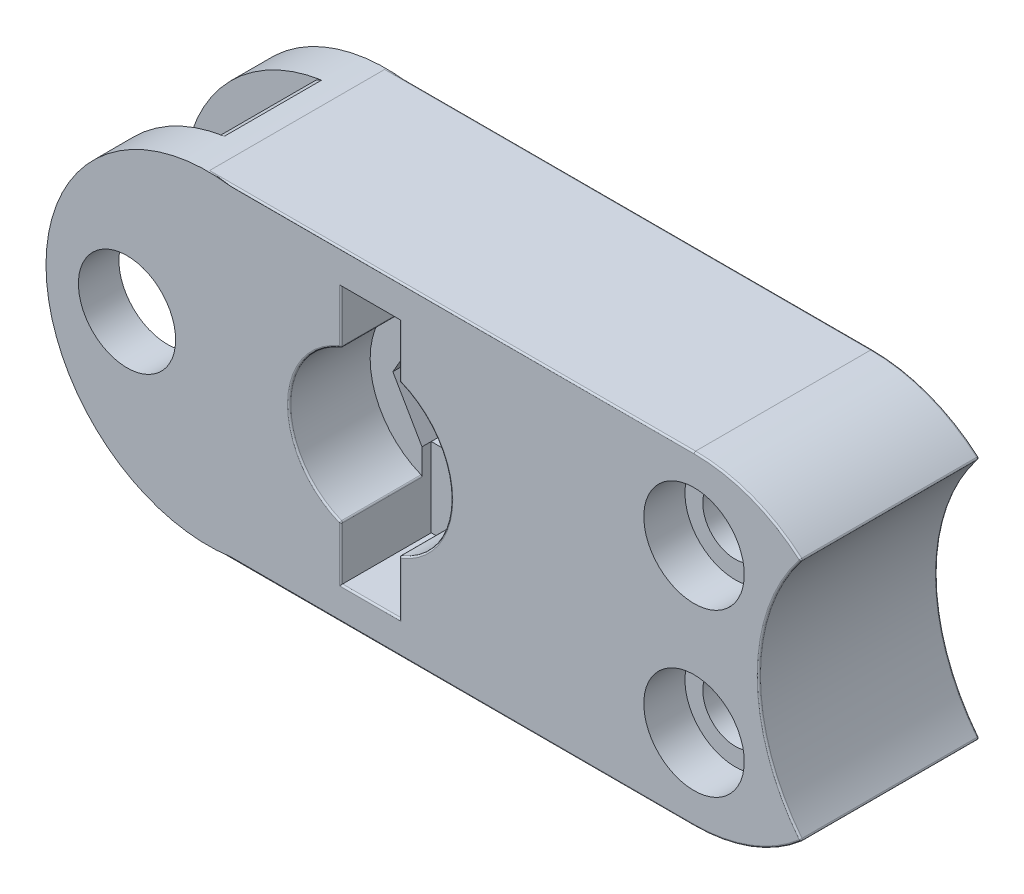
SolidWorks part; units mm, degrees
ref_plane "前视基准面" through (0, 0, 0) normal (0, 0, 1) x (1, 0, 0)
ref_plane "上视基准面" through (0, 0, 0) normal (0, 1, 0) x (1, 0, 0)
ref_plane "右视基准面" through (0, 0, 0) normal (1, 0, 0) x (0, 0, -1)
sketch "草图1" plane through (0, 0, 0) normal (0, 0, 1) x (1, 0, 0)
  line L0 (-100.0924, 0) -> (199.9076, 0) construction
  line L1 (-100.0924, 100) -> (199.9076, 100)
  line L2 (-100.0924, -100) -> (199.9076, -100)
  arc A0 (-100.0924, 100) -> (-100.0924, -100) centre (-100.0924, 0) ccw
  arc A1 (199.9076, -100) -> (199.9076, 100) centre (199.9076, 0) ccw
  circle A2 centre (-110.0924, 0) radius 40
  point P3 (49.9076, 0)
  point P10 (-200.0924, 0)
  dimension "D3" = 90
  dimension "D1" = 300
  dimension "D2" = 200
extrude "凸台-拉伸1" add sketch "草图1" along normal blind 110
ref_plane "基准面4" through (-100, 0, 0) normal (1, 0, 0) x (0, 0, -1)
sketch "草图2" plane through (-100, 0, 0) normal (1, 0, 0) x (0, 0, -1)
  line L0 (-110, 100) -> (-110, -100) construction
  circle A0 centre (-95, 0) radius 3
  circle A1 centre (-75, 0) radius 3
  circle A2 centre (-55, 0) radius 3
  dimension "D1" = 6
  dimension "D2" = 15
  dimension "D3" = 3
extrude "切除-拉伸2" cut sketch "草图2" against normal blind 150
sketch "草图3" plane through (0, 0, 110) normal (0, 0, 1) x (1, 0, 0)
  circle A0 centre (0, 0) radius 50
  dimension "D1" = 0
extrude "切除-拉伸3" cut sketch "草图3" against normal blind 50
sketch "草图4" plane through (0, 0, 60) normal (0, 0, 1) x (1, 0, 0)
  line L1 (36, 0) -> (18, 31.1769)
  line L2 (18, 31.1769) -> (-18, 31.1769)
  line L3 (-18, 31.1769) -> (-36, 0)
  line L4 (-36, 0) -> (-18, -31.1769)
  line L5 (-18, -31.1769) -> (18, -31.1769)
  line L6 (18, -31.1769) -> (36, 0)
  circle A0 centre (0, 0) radius 36 construction
extrude "切除-拉伸4" cut sketch "草图4" against normal blind 10
sketch "草图5" plane through (0, 0, 50) normal (0, 0, 1) x (1, 0, 0)
  line L1 (18, 80) -> (-18, 80)
  line L2 (18, 80) -> (18, -80)
  line L3 (18, -80) -> (-18, -80)
  line L4 (-18, 80) -> (-18, -80)
  line L5 (18, 80) -> (-18, -80) construction
  line L6 (18, -80) -> (-18, 80) construction
  point P0 (0, 0)
  dimension "D1" = 36
  dimension "D2" = 160
extrude "切除-拉伸7" cut sketch "草图5" along normal blind 122
sketch "草图6" plane through (0, 0, 50) normal (0, 0, 1) x (1, 0, 0)
  line L1 (36, 0) -> (18, 31.1769)
  line L2 (18, 31.1769) -> (-18, 31.1769)
  line L3 (-18, 31.1769) -> (-36, 0)
  line L4 (-36, 0) -> (-18, -31.1769)
  line L5 (-18, -31.1769) -> (18, -31.1769)
  line L6 (18, -31.1769) -> (36, 0)
  circle A0 centre (0, 0) radius 36 construction
extrude "切除-拉伸8" cut sketch "草图6" against normal blind 10
sketch "草图7" plane through (0, 0, 50) normal (0, 0, 1) x (1, 0, 0)
  line L0 (-18, 80) -> (18, 80) construction
  circle A0 centre (0, 62) radius 3
  point P4 (0, 80)
  dimension "D1" = 6
  dimension "D2" = 18
extrude "切除-拉伸9" cut sketch "草图7" against normal blind 10
mirror "镜向1" about plane through (0, 0, 0) normal (0, 1, 0) of "切除-拉伸9"
sketch "草图8" plane through (0, 0, 110) normal (0, 0, 1) x (1, 0, 0)
  line L0 (199.9076, 100) -> (199.9076, -100)
  line L1 (199.9076, -100) -> (199.9076, 0)
  line L2 (199.9076, 0) -> (199.9076, 100)
  circle A0 centre (199.9076, 50) radius 12.5
  dimension "D1" = 25
extrude "切除-拉伸12" cut sketch "草图8" against normal blind 200 contours L2 A0 | L2 A0
sketch "草图9" plane through (0, 0, 110) normal (0, 0, 1) x (1, 0, 0)
  circle A0 centre (199.9076, 50) radius 31
  circle M2 centre (199.9076, 50) radius 12.5
extrude "切除-拉伸13" cut sketch "草图9" against normal blind 25.4 contours A0 M2
ref_plane "基准面5" through (0, 0, 55) normal (0, 0, 1) x (1, 0, 0)
mirror "镜向3" about plane through (0, 0, 0) normal (0, 1, 0) of "切除-拉伸13", "切除-拉伸12" second plane through (0, 0, 55) second plane normal (0, 0, 1)
sketch "草图10" plane through (0, 0, 40) normal (0, 0, 1) x (1, 0, 0)
  line L1 (36, 0) -> (18, 31.1769)
  line L2 (18, 31.1769) -> (-18, 31.1769)
  line L3 (-18, 31.1769) -> (-36, 0)
  line L4 (-36, 0) -> (-18, -31.1769)
  line L5 (-18, -31.1769) -> (18, -31.1769)
  line L6 (18, -31.1769) -> (36, 0)
  line L7 (-18, 83.4512) -> (18, 83.4512)
  line L8 (-18, 83.4512) -> (-18, -83.4512)
  line L9 (-18, -83.4512) -> (18, -83.4512)
  line L10 (18, 83.4512) -> (18, -83.4512)
  line L11 (-18, 83.4512) -> (18, -83.4512) construction
  line L12 (-18, -83.4512) -> (18, 83.4512) construction
  circle A0 centre (0, 0) radius 36 construction
  circle A1 centre (0, 0) radius 36
  circle A2 centre (0, 0) radius 50
  line M7 (18, -31.1769) -> (36, 0)
  line M8 (36, 0) -> (18, 31.1769)
  line M10 (-18, 31.1769) -> (-36, 0)
  line M11 (-36, 0) -> (-18, -31.1769)
extrude "凸台-拉伸2" add sketch "草图10" along normal blind 4.3 contours L10 A2 A1 | L8 A2 A1 | A1 M8 | A1 M7 | A1 M11 | A1 M10
sketch "草图11" plane through (0, 0, 50) normal (0, 0, 1) x (1, 0, 0)
  line L0 (-18, 31.1769) -> (18, 31.1769)
  line L1 (-18, 80) -> (18, 80)
  line L2 (-18, 80) -> (-18, -80)
  line L3 (-18, -80) -> (18, -80)
  line L4 (18, 80) -> (18, -80)
  line L5 (-18, 80) -> (18, -80) construction
  line L6 (-18, -80) -> (18, 80) construction
  circle A0 centre (0, 62) radius 3
  point P0 (0, 0)
  circle M1 centre (0, 62) radius 3
  line M2 (-18, 31.1769) -> (18, 31.1769)
  line M3 (18, 31.1769) -> (18, 80)
  line M4 (18, 80) -> (-18, 80)
  line M5 (-18, 80) -> (-18, 31.1769)
extrude "凸台-拉伸3" add sketch "草图11" along normal blind 4.3 contours M5 M2 M3 M4 M1
mirror "镜向4" about plane through (0, 0, 0) normal (0, 1, 0) of "凸台-拉伸3"
sketch "草图12" plane through (0, 0, 110) normal (0, 0, 1) x (1, 0, 0)
  line L0 (199.9076, 100) -> (199.9076, -100)
  line L1 (199.9076, 0) -> (359.9076, 0)
  circle A0 centre (359.9076, 0) radius 120
  arc M6 (199.9076, -100) -> (199.9076, 100) centre (199.9076, 0) ccw
  dimension "D1" = 160
extrude "切除-拉伸14" cut sketch "草图12" against normal blind 200 contours L1 A0 M6 | A0 L1 M6
sketch "草图13" plane through (0, 0, 84.6) normal (0, 0, 1) x (1, 0, 0)
  circle A0 centre (199.9076, 50) radius 20
extrude "切除-拉伸15" cut sketch "草图13" against normal blind 200
mirror "镜向5" about plane through (0, 0, 0) normal (0, 1, 0) of "切除-拉伸15"
sketch "草图14" plane through (0, 0, 110) normal (0, 0, 1) x (1, 0, 0)
  circle A0 centre (-70.0924, 0) radius 108.5853
  circle A1 centre (-110.0924, 0) radius 40 construction
  arc M5 (-100.0924, 100) -> (-100.0924, -100) centre (-100.0924, 0) ccw
extrude "切除-拉伸16" cut sketch "草图14" against normal blind 200 contours A0 M5
fillet "圆角1" radius 1 16 edges at (-107.5362, -99.7226, 0) (49.9076, -100, 0) (-107.5362, 99.7226, 0) (49.9076, 100, 0) (-107.5362, -99.7226, 110) (49.9076, -100, 110) (-107.5362, 99.7226, 110) (49.9076, 100, 110) (235.3292, -93.5164, 0) (239.9076, 0, 0) (235.3292, 93.5164, 0) (266.1576, 74.9062, 55) (266.1576, -74.9062, 55) (235.3292, -93.5164, 110) (239.9076, 0, 110) (235.3292, 93.5164, 110)
fillet "圆角2" radius 1 11 edges at (18, -46.6476, 85) (18, 46.6476, 85) (18, 63.3238, 110) (-18, 63.3238, 110) (-18, -46.6476, 85) (-18, 46.6476, 85) (-50, 0, 110) (-18, -63.3238, 110) (0, -80, 110) (18, -63.3238, 110) (50, 0, 110)
sketch "草图18" plane through (0, 0, 110) normal (0, 0, 1) x (1, 0, 0)
  circle A0 centre (-110.0924, 0) radius 127.2546
  circle A1 centre (-162.4332, 0) radius 108.3882
  arc M10 (-118.2554, 97.3196) -> (-118.2554, -97.3196) centre (-70.0924, 0) ccw
  arc M11 (-118.2554, -97.3196) -> (-100.0924, -99) centre (-100.0924, 0) ccw
  arc M17 (-100.0924, 99) -> (-118.2554, 97.3196) centre (-100.0924, 0) ccw
  circle M20 centre (-110.0924, 0) radius 40
extrude "凸台-拉伸6" add sketch "草图18" against normal blind 110 contours A1 M11 M17 M10 M20 | M20
sketch "草图19" plane through (0, 0, 110) normal (0, 0, 1) x (1, 0, 0)
  line L0 (-100.0924, 99) -> (-100.0924, -100)
  circle A0 centre (-100.0924, 0) radius 100
  arc M1 (-100.0924, 99) -> (-118.2554, 97.3196) centre (-100.0924, 0) ccw
  arc M2 (-118.2554, 97.3196) -> (-118.2554, -97.3196) centre (-70.0924, 0) ccw
  arc M3 (-118.2554, -97.3196) -> (-100.0924, -99) centre (-100.0924, 0) ccw
extrude "切除-拉伸20" cut sketch "草图19" against normal blind 110 contours L0 M1 M2 M3
sketch "草图20" plane through (0, 0, 110) normal (0, 0, 1) x (1, 0, 0)
  line L0 (-100.0924, 99) -> (-100.0924, -99) construction
  line L1 (-100.0924, 99) -> (-100.0924, -99)
  circle A0 centre (-100.0924, 0) radius 100
  line M11 (199.9076, 99) -> (-100.0924, 99)
  line M12 (-100.0924, 99) -> (-100.0924, -99)
  line M13 (-100.0924, -99) -> (199.9076, -99)
extrude "凸台-拉伸7" add sketch "草图20" against normal blind 25 contours A0 M11 M13 M12
sketch "草图21" plane through (0, 0, 110) normal (0, 0, 1) x (1, 0, 0)
  line L0 (-100.0924, 100) -> (-100.0924, -100)
  line L1 (-100.0924, -100) -> (-100.0924, 0)
  line L2 (-100.0924, 0) -> (-200.0924, 0)
  arc A0 (-85.9857, 99) -> (-85.9857, -99) centre (-100.0924, 0) ccw construction
  circle A1 centre (-150.0924, 0) radius 30
  dimension "D1" = 60
extrude "切除-拉伸21" cut sketch "草图21" against normal blind 25 contours L2 A1 | L2 A1
mirror "镜向7" about plane through (0, 0, 55) normal (0, 0, 1) of "凸台-拉伸7", "切除-拉伸21"
